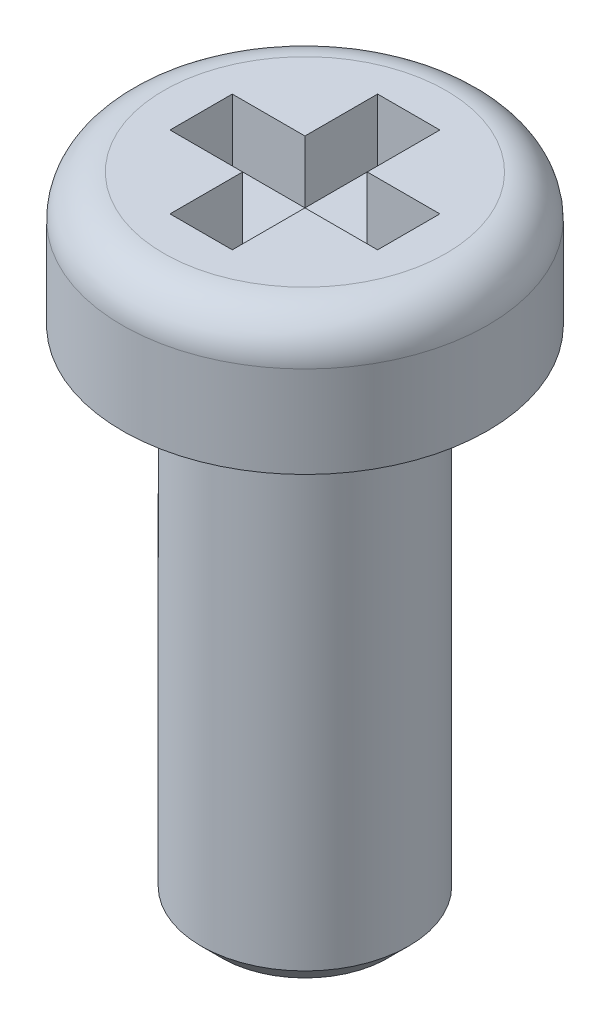
SolidWorks part; units mm, degrees
material "Nylon 101"
ref_plane "Front Plane" through (0, 0, 0) normal (0, 0, 1) x (1, 0, 0)
ref_plane "Top Plane" through (0, 0, 0) normal (0, 1, 0) x (1, 0, 0)
ref_plane "Right Plane" through (0, 0, 0) normal (1, 0, 0) x (0, 0, -1)
sketch "Sketch1" plane through (0, 0, 0) normal (0, 0, 1) x (1, 0, 0)
  line L0 (0, -138.0872) -> (0, 6766.2712) construction
  line L1 (0, 0) -> (-2.2, 0)
  line L2 (-2.2, 0) -> (-2.2, -1.6)
  line L3 (-2.2, -1.6) -> (-1.25, -1.6)
  line L4 (-1.25, -1.6) -> (-1.25, -7.7)
  line L5 (-1.25, -7.7) -> (0, -7.7)
  line L6 (0, -7.7) -> (0, 0)
  dimension "D1" = 7.7
  dimension "D2" = 4.4
  dimension "D3" = 2.5
  dimension "D4" = 6.1
revolve "Revolve1" add sketch "Sketch1" angle 360 about L0
chamfer "Chamfer1" distance 0.25 angle 45 1 edges at (1.25, -7.7, 0)
fillet "Fillet1" radius 0.5 1 edges at (2.2, 0, 0)
sketch "Sketch2" plane through (0, 0, 0) normal (0, 1, 0) x (1, 0, 0)
  line L0 (-0.375, 0.375) -> (-0.375, 1.25)
  line L1 (-0.375, -1.25) -> (0.375, -1.25)
  line L2 (-0.375, -1.25) -> (-0.375, -0.375)
  line L3 (-0.375, 1.25) -> (0.375, 1.25)
  line L4 (0.375, -1.25) -> (0.375, -0.375)
  line L5 (-0.375, -1.25) -> (0.375, 1.25) construction
  line L6 (-0.375, 1.25) -> (0.375, -1.25) construction
  line L7 (-1.25, -0.375) -> (-0.375, -0.375)
  line L8 (-1.25, -0.375) -> (-1.25, 0.375)
  line L9 (-1.25, 0.375) -> (-0.375, 0.375)
  line L10 (1.25, -0.375) -> (1.25, 0.375)
  line L11 (-1.25, -0.375) -> (1.25, 0.375) construction
  line L12 (-1.25, 0.375) -> (1.25, -0.375) construction
  line L13 (0.375, 0.375) -> (1.25, 0.375)
  line L14 (0.375, 0.375) -> (0.375, 1.25)
  line L15 (0.375, -0.375) -> (1.25, -0.375)
  point P0 (0, 0)
  point P6 (0, 0)
  dimension "D1" = 0.75
  dimension "D2" = 0.75
  dimension "D3" = 2.5
  dimension "D4" = 2.5
extrude "Cut-Extrude1" cut sketch "Sketch2" against normal blind 0.75
